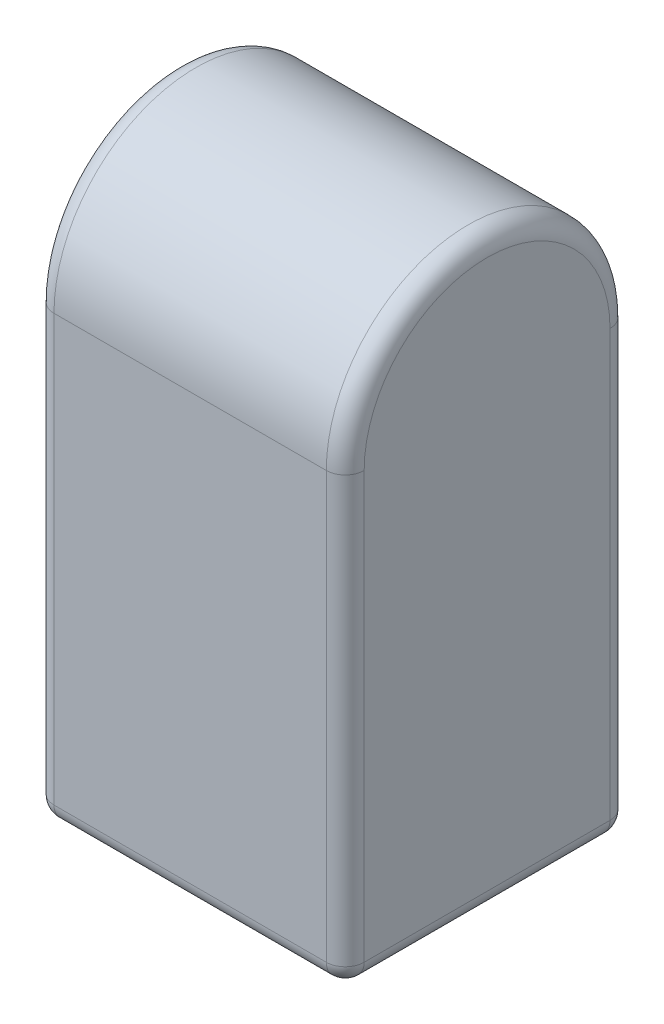
SolidWorks part; units mm, degrees
ref_plane "Front Plane" through (0, 0, 0) normal (0, 0, 1) x (1, 0, 0)
ref_plane "Top Plane" through (0, 0, 0) normal (0, 1, 0) x (1, 0, 0)
ref_plane "Right Plane" through (0, 0, 0) normal (1, 0, 0) x (0, 0, -1)
sketch "Sketch1" plane through (0, 0, 0) normal (1, 0, 0) x (0, 0, -1)
  line L0 (-14.986, 46.99) -> (-14.986, 0)
  line L1 (-14.986, 0) -> (14.986, 0)
  line L2 (14.986, 0) -> (14.986, 46.99)
  arc A0 (-14.986, 46.99) -> (14.986, 46.99) centre (0, 46.99) cw
  point P5 (0, 0)
  point P6 (0, 0)
  point P8 (0, 61.976)
  dimension "D1" = 61.976
  dimension "D2" = 29.972
extrude "Boss-Extrude1" add sketch "Sketch1" along normal mid plane 32.766
fillet "Fillet1" radius 2 10 edges at (-16.383, 23.495, -14.986) (-16.383, 23.495, 14.986) (16.383, 23.495, -14.986) (16.383, 23.495, 14.986) (0, 0, 14.986) (16.383, 0, 0) (0, 0, -14.986) (-16.383, 0, 0) (-16.383, 61.976, 0) (16.383, 61.976, 0)
